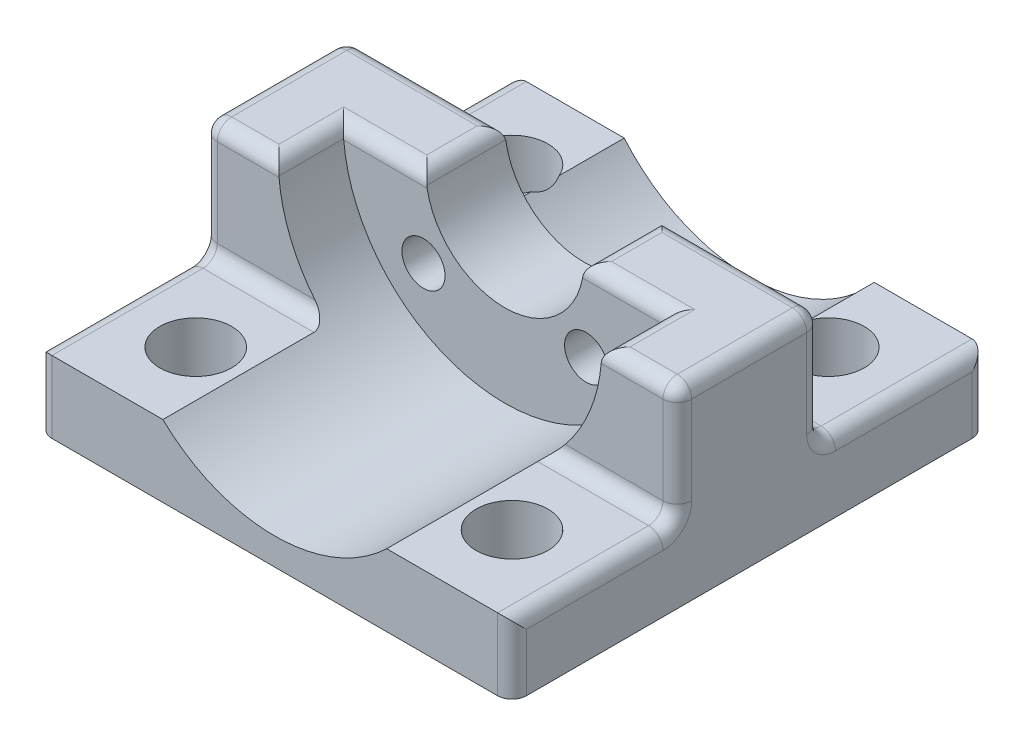
SolidWorks part; units mm, degrees
ref_plane "Front Plane" through (0, 0, 0) normal (0, 0, 1) x (1, 0, 0)
ref_plane "Top Plane" through (0, 0, 0) normal (0, 1, 0) x (1, 0, 0)
ref_plane "Right Plane" through (0, 0, 0) normal (1, 0, 0) x (0, 0, -1)
sketch "Sketch3" plane through (0, 0, 0) normal (0, 0, 1) x (1, 0, 0)
  line L0 (16.5, 0) -> (-16.5, 0)
  line L1 (-16.5, 0) -> (-16.5, 13.123)
  line L2 (-16.5, 13.123) -> (-5.5, 13.123) construction
  line L3 (0, 7.623) -> (0, 0) construction
  line L4 (-16.5, 13.123) -> (-11.5, 13.123)
  line L5 (-11.5, 13.123) -> (-5.5, 13.123)
  line L6 (0, 7.623) -> (0, 0) construction
  line L7 (16.5, 13.123) -> (5.5, 13.123) construction
  line L8 (11.5, 13.123) -> (5.5, 13.123)
  line L9 (16.5, 13.123) -> (11.5, 13.123)
  line L10 (16.5, 0) -> (16.5, 13.123)
  circle A0 centre (0, 13.123) radius 11.5 construction
  circle A1 centre (0, 13.123) radius 5.5
  dimension "D1" = 23
  dimension "D4" = 11
  dimension "D2" = 5
  dimension "D3" = 13.123
extrude "Boss-Extrude1" add sketch "Sketch3" along normal blind 10 contours A1 L5 L4 L1 L0 L10 L9 L8
sketch "Sketch6" plane through (0, 0, 0) normal (0, -1, 0) x (-1, 0, 0)
  line L0 (0, -10) -> (0, 0) construction
  line L1 (-16.5, -10) -> (16.5, -10) construction
  line L3 (-16.5, 11.5) -> (16.5, 11.5)
  line L4 (-16.5, 11.5) -> (-16.5, -21.5)
  line L5 (-16.5, -21.5) -> (16.5, -21.5)
  line L6 (16.5, 11.5) -> (16.5, -21.5)
  line L7 (-16.5, 11.5) -> (16.5, -21.5) construction
  line L8 (-16.5, -21.5) -> (16.5, 11.5) construction
  line L10 (-11, 6) -> (11, 6) construction
  line L11 (-11, 6) -> (-11, -16) construction
  line L12 (-11, -16) -> (11, -16) construction
  line L13 (11, 6) -> (11, -16) construction
  line L14 (-11, 6) -> (11, -16) construction
  line L15 (-11, -16) -> (11, 6) construction
  circle A0 centre (11, -16) radius 2.5
  circle A1 centre (-11, -16) radius 2.5
  circle A2 centre (-11, 6) radius 2.5
  circle A3 centre (11, 6) radius 2.5
  point P5 (0, -5)
  point P10 (0, -5)
  dimension "D2" = 5
  dimension "D1" = 22
extrude "Boss-Extrude2" add sketch "Sketch6" against normal blind 5
sketch "Sketch4" plane through (0, 0, 21.5) normal (0, 0, 1) x (1, 0, 0)
  circle A0 centre (0, 13.123) radius 11.25
  dimension "D1" = 22.5
extrude "Cut-Extrude1" cut sketch "Sketch4" against normal blind 16
sketch "Sketch5" plane through (0, 0, 5.5) normal (0, 0, 1) x (1, 0, 0)
  line L0 (0, 13.123) -> (0, 5.123) construction
  line L1 (0, 13.123) -> (-5.6569, 7.4661) construction
  line L2 (0, 13.123) -> (5.6569, 7.4661) construction
  circle A0 centre (0, 13.123) radius 8 construction
  circle A1 centre (-5.6569, 7.4661) radius 1.5
  circle A2 centre (5.6569, 7.4661) radius 1.5
  dimension "D1" = 16
  dimension "D3" = 3
  dimension "D2" = 45
extrude "Cut-Extrude2" cut sketch "Sketch5" against normal up to next
sketch "Sketch7" plane through (0, 0, 0) normal (0, 0, -1) x (-1, 0, 0)
  circle A0 centre (0, 12.3726) radius 11.3996
extrude "Cut-Extrude3" cut sketch "Sketch7" along normal up to next
fillet "Fillet1" radius 1 28 edges at (16.5, 5, 15.75) (16.5, 5, -5.75) (-13.875, 13.123, 10) (-16.5, 13.123, 5) (-11, 13.123, 0) (-5.5, 13.123, 2.75) (-8.375, 13.123, 5.5) (-11.25, 13.123, 7.75) (5.5, 13.123, 2.75) (11, 13.123, 0) (16.5, 13.123, 5) (13.875, 13.123, 10) (11.25, 13.123, 7.75) (8.375, 13.123, 5.5) (16.5, 9.0615, 10) (16.5, 9.0615, 0) (16.5, 2.5, 21.5) (-16.5, 2.5, 21.5) (12.1416, 5, 10) (-12.1416, 5, 10) (-16.5, 2.5, -11.5) (16.5, 2.5, -11.5) (12.5973, 5, 0) (-12.5973, 5, 0) (-16.5, 9.0615, 10) (-16.5, 9.0615, 0) (-16.5, 5, 15.75) (-16.5, 5, -5.75)
